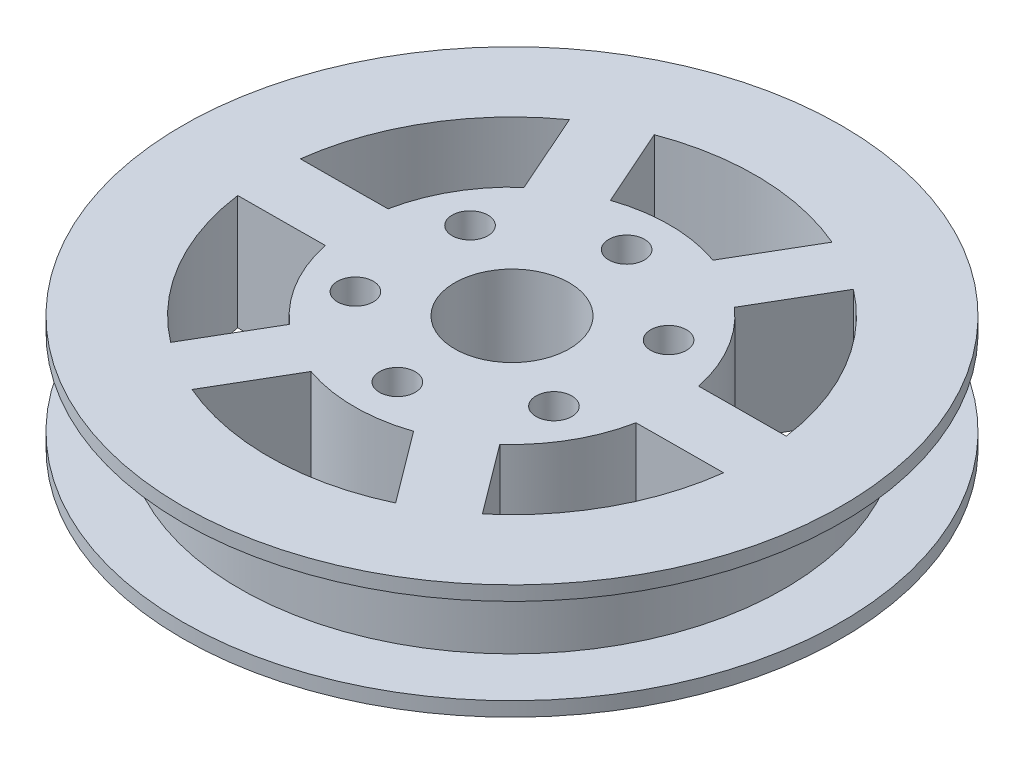
SolidWorks part; units mm, degrees
material "2024 Alloy"
ref_plane "Front Plane" through (0, 0, 0) normal (0, 0, 1) x (1, 0, 0)
ref_plane "Top Plane" through (0, 0, 0) normal (0, 1, 0) x (1, 0, 0)
ref_plane "Right Plane" through (0, 0, 0) normal (1, 0, 0) x (0, 0, -1)
sketch "Sketch2" plane through (0, 0, 0) normal (0, 1, 0) x (1, 0, 0)
  circle A0 centre (0, 0) radius 60.325
  circle A1 centre (0, 0) radius 25.4
  circle A2 centre (0, 25.4) radius 3.9688
  circle A3 centre (21.997, 12.7) radius 3.9688
  circle A4 centre (21.997, -12.7) radius 3.9688
  circle A5 centre (0, -25.4) radius 3.9688
  circle A6 centre (-21.997, -12.7) radius 3.9688
  circle A7 centre (-21.997, 12.7) radius 3.9688
  circle A8 centre (0, 0) radius 12.7
  point P19 (0, 0)
  dimension "D2" = 120.65
  dimension "D3" = 50.8
  dimension "D4" = 7.9375
  dimension "D5" = 25.4
  dimension "D1" = 6
extrude "Boss-Extrude1" add sketch "Sketch2" along normal blind 19.05 contours A0 A7 A1 A2 A3 A4 A5 A6 | A7 A1 A6 A5 A4 A3 A2
sketch "Sketch3" plane through (0, 19.05, 0) normal (0, 1, 0) x (1, 0, 0)
  circle A0 centre (0, 25.4) radius 3.9688 construction
  circle A1 centre (21.997, 12.7) radius 3.9688 construction
  circle A2 centre (21.997, -12.7) radius 3.9688 construction
  circle A3 centre (0, -25.4) radius 3.9688 construction
  circle A4 centre (-21.997, -12.7) radius 3.9688 construction
  circle A5 centre (0, 0) radius 12.7 construction
  circle A6 centre (-21.997, 12.7) radius 3.9688 construction
  circle A7 centre (0, 25.4) radius 3.9688
  circle A8 centre (21.997, 12.7) radius 3.9688
  circle A9 centre (21.997, -12.7) radius 3.9688
  circle A10 centre (0, -25.4) radius 3.9688
  circle A11 centre (-21.997, -12.7) radius 3.9688
  circle A12 centre (0, 0) radius 12.7
  circle A13 centre (-21.997, 12.7) radius 3.9688
  circle A14 centre (0, 0) radius 73.025
  dimension "D1" = 146.05
extrude "Boss-Extrude2" add sketch "Sketch3" along normal blind 3.175
sketch "Sketch4" plane through (0, 0, 0) normal (0, -1, 0) x (1, 0, 0)
  circle A0 centre (0, 0) radius 12.7 construction
  circle A1 centre (-21.997, -12.7) radius 3.9688 construction
  circle A2 centre (0, -25.4) radius 3.9688 construction
  circle A3 centre (21.997, -12.7) radius 3.9688 construction
  circle A4 centre (21.997, 12.7) radius 3.9688 construction
  circle A5 centre (0, 25.4) radius 3.9688 construction
  circle A6 centre (-21.997, 12.7) radius 3.9688 construction
  circle A7 centre (0, 0) radius 12.7
  circle A8 centre (-21.997, -12.7) radius 3.9688
  circle A9 centre (0, -25.4) radius 3.9688
  circle A10 centre (21.997, -12.7) radius 3.9688
  circle A11 centre (21.997, 12.7) radius 3.9688
  circle A12 centre (0, 25.4) radius 3.9688
  circle A13 centre (-21.997, 12.7) radius 3.9688
  circle A14 centre (0, 0) radius 73.025 construction
  circle A15 centre (0, 0) radius 73.025
extrude "Boss-Extrude3" add sketch "Sketch4" along normal blind 3.175
sketch "Sketch6" plane through (0, 0, 0) normal (0, 1, 0) x (1, 0, 0)
  line L6 (-21.3143, -49.5883) -> (-11.5918, -32.9452)
  line L7 (-31.2839, 43.9843) -> (-23.3122, 26.0057)
  line L8 (-53.4791, -7.2996) -> (-34.1777, -7.1861)
  line L9 (-32.7272, -42.9212) -> (-23.0047, -26.2781)
  line L10 (-18.9967, 50.5215) -> (-11.2551, 33.0617)
  line L11 (-53.5613, 6.6701) -> (-34.2599, 6.7836)
  line L20 (11.5918, 32.9452) -> (21.3143, 49.5883)
  line L25 (23.0047, 26.2781) -> (32.7272, 42.9212)
  line L27 (34.1777, 7.1861) -> (53.4791, 7.2996)
  line L32 (34.2599, -6.7836) -> (53.5613, -6.6701)
  line L34 (23.3122, -26.0057) -> (34.7428, -41.3067)
  line L37 (11.2551, -33.0617) -> (23.0254, -48.8173)
  circle A0 centre (0, 0) radius 34.925
  circle A1 centre (0, 0) radius 53.975
  circle A3 centre (0, 0) radius 53.975
  circle A4 centre (0, 0) radius 34.925
  point P14 (0, 0)
  dimension "D1" = 69.85
  dimension "D2" = 107.95
extrude "Cut-Extrude1" cut sketch "Sketch6" against normal through all both and the other way through all
